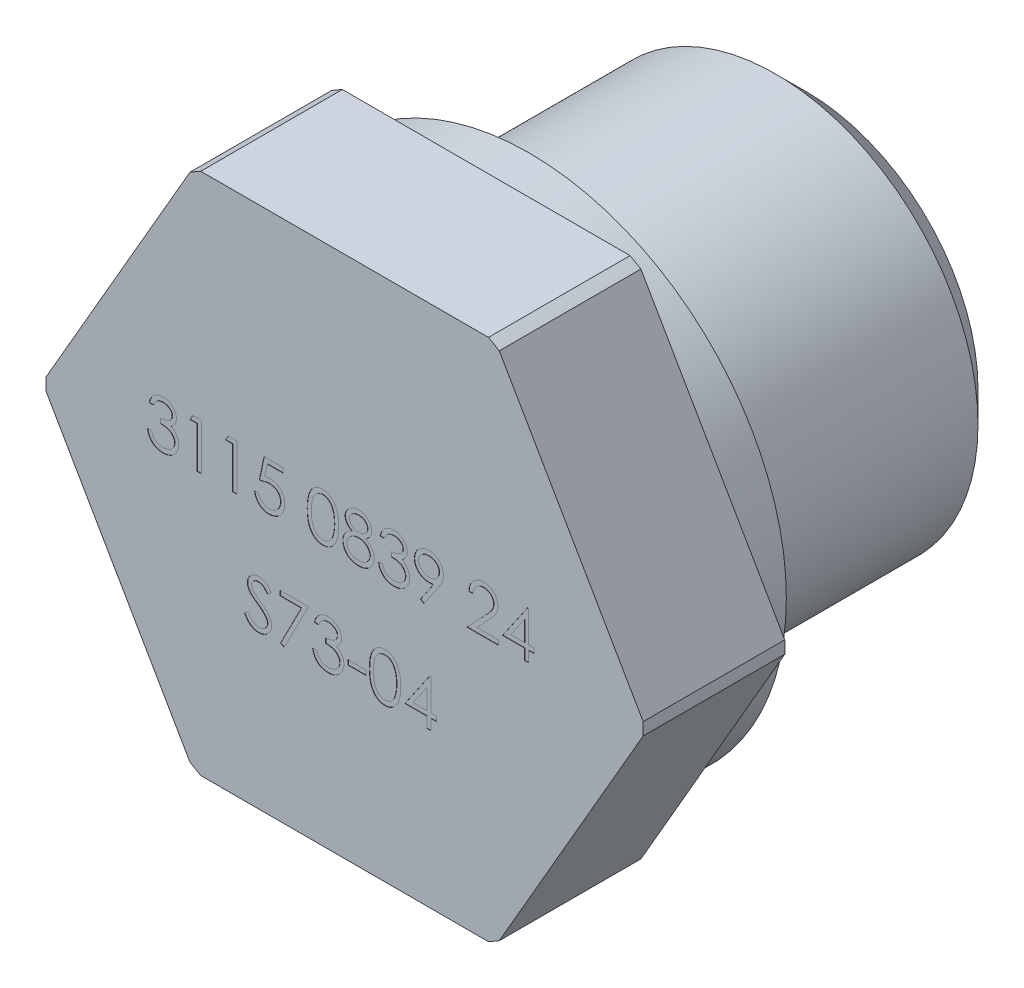
SolidWorks part; units mm, degrees
material "Plain Carbon Steel"
ref_plane "Front Plane" through (0, 0, 0) normal (0, 0, 1) x (1, 0, 0)
ref_plane "Top Plane" through (0, 0, 0) normal (0, 1, 0) x (1, 0, 0)
ref_plane "Right Plane" through (0, 0, 0) normal (1, 0, 0) x (0, 0, -1)
sketch "Sketch1" plane through (0, 0, 0) normal (1, 0, 0) x (0, 0, -1)
  line L0 (0, 0) -> (18.9659, 0) construction
  line L1 (15, 0) -> (15, 5.575)
  line L2 (15, 5.575) -> (14, 6.575)
  line L3 (6, 8.35) -> (4.6, 8.35)
  line L4 (4.6, 8.35) -> (4.6, 9.7)
  line L5 (4.6, 9.7) -> (0, 9.7)
  line L6 (0, 9.7) -> (0, 0)
  line L7 (6, 8.35) -> (6, 6.575)
  line L8 (6, 6.575) -> (14, 6.575)
  line L9 (0, 0) -> (15, 0)
  dimension "D1" = 19.4
  dimension "D2" = 4.6
  dimension "D3" = 6
  dimension "D4" = 13.15
  dimension "D5" = 15
  dimension "D6" = 1
  dimension "D7" = 45
  dimension "D8" = 16.7
revolve "Revolve1" add sketch "Sketch1" angle 360 about L0
cosmetic thread "Cosmetic Thread1" parameters "D2"=11.44
sketch "Sketch2" plane through (0, 0, 0) normal (0, 0, 1) x (1, 0, 0)
  line L1 (-4.9075, 8.5) -> (-9.815, 0)
  line L2 (-9.815, 0) -> (-4.9075, -8.5)
  line L3 (-4.9075, -8.5) -> (4.9075, -8.5)
  line L4 (4.9075, -8.5) -> (9.815, 0)
  line L5 (9.815, 0) -> (4.9075, 8.5)
  line L6 (4.9075, 8.5) -> (-4.9075, 8.5)
  circle A0 centre (0, 0) radius 8.5 construction
  dimension "D1" = 17
extrude "Cut-Extrude2" cut sketch "Sketch2" against normal up to next (15 mm away) flip side to cut
sketch "Sketch3" plane through (0, 0, 0) normal (0, 0, 1) x (1, 0, 0)
  line L0 (-7.3259, 0) -> (7.0907, 0) construction
  text T0 "3115 0839 24\r\nS73-04" font "Century Gothic" height 1.5
extrude "Cut-Extrude3" cut sketch "Sketch3" against normal blind 0.01
